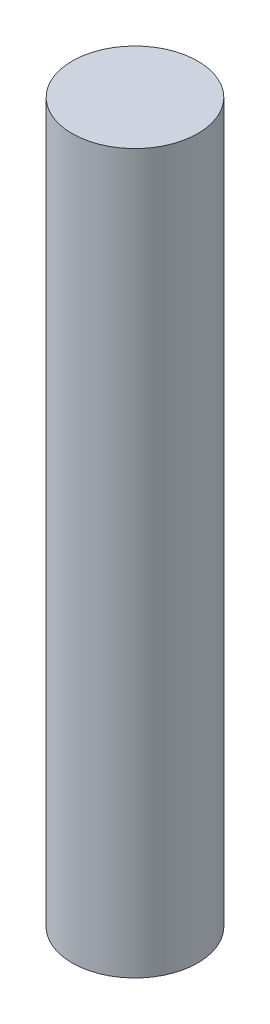
SolidWorks part; units mm, degrees
ref_plane "Front Plane" through (0, 0, 0) normal (0, 0, 1) x (1, 0, 0)
ref_plane "Top Plane" through (0, 0, 0) normal (0, 1, 0) x (1, 0, 0)
ref_plane "Right Plane" through (0, 0, 0) normal (1, 0, 0) x (0, 0, -1)
sketch "Sketch1" plane through (0, 0, 0) normal (0, 1, 0) x (1, 0, 0)
  circle A0 centre (0, 0) radius 5
  dimension "D1" = 10
extrude "Boss-Extrude1" add sketch "Sketch1" along normal blind 57.15
